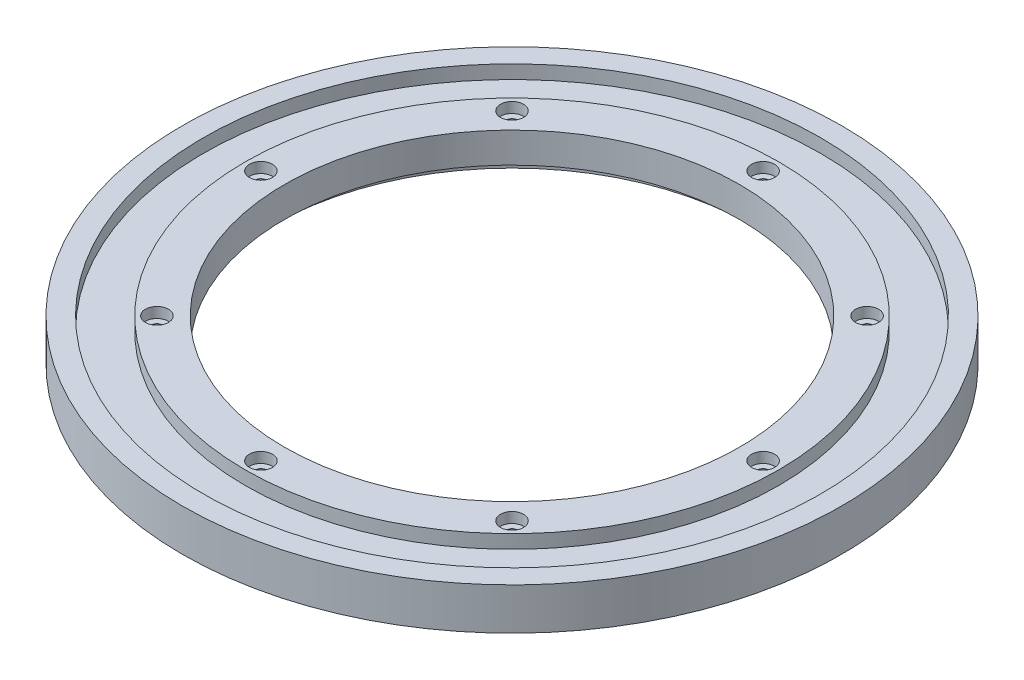
SolidWorks part; units mm, degrees
ref_plane "Front Plane" through (0, 0, 0) normal (0, 0, 1) x (1, 0, 0)
ref_plane "Top Plane" through (0, 0, 0) normal (0, 1, 0) x (1, 0, 0)
ref_plane "Right Plane" through (0, 0, 0) normal (1, 0, 0) x (0, 0, -1)
sketch "Sketch3" plane through (0, 0, 0) normal (1, 0, 0) x (0, 0, -1)
  line L0 (0, -1465.1364) -> (0, 71791.6854) construction
  line L1 (-315, 34.7123) -> (-295, 34.7123)
  line L2 (-295, 34.7123) -> (-295, 21.7123)
  line L3 (-295, 21.7123) -> (-255, 21.7123)
  line L4 (-255, 21.7123) -> (-255, 34.7123)
  line L5 (-255, 34.7123) -> (-217.5, 34.7123)
  line L6 (-217.5, 34.7123) -> (-217.5, 5.7123)
  line L7 (-217.5, 5.7123) -> (-229.5, 5.7123)
  line L8 (-229.5, 5.7123) -> (-229.5, -5.2877)
  line L9 (-229.5, -5.2877) -> (-315, -5.2877)
  line L10 (-315, -5.2877) -> (-315, 34.7123)
  dimension "D1" = 40
  dimension "D2" = 12
  dimension "D3" = 29
  dimension "D4" = 37.5
  dimension "D5" = 40
  dimension "D6" = 13
  dimension "D7" = 11
  dimension "D8" = 20
  dimension "D9" = 510
  dimension "D10" = 590
  dimension "D11" = 27
revolve "Revolve1" add sketch "Sketch3" angle 360 about L0
sketch "Sketch4" plane through (0, 34.7123, 0) normal (0, 1, 0) x (1, 0, 0)
  line L0 (0, -1000) -> (0, 49000) construction
  line L1 (-1000, 0) -> (49000, 0) construction
  circle A0 centre (0, 240) radius 5
  circle A1 centre (0, 0) radius 217.5 construction
  circle A2 centre (169.7056, 169.7056) radius 5
  circle A3 centre (240, 0) radius 5
  circle A4 centre (169.7056, -169.7056) radius 5
  circle A5 centre (0, -240) radius 5
  circle A6 centre (-169.7056, -169.7056) radius 5
  circle A7 centre (-240, 0) radius 5
  circle A8 centre (-169.7056, 169.7056) radius 5
  point P27 (0, 0)
  dimension "D1" = 10
  dimension "D2" = 240
  dimension "D3" = 8
extrude "Cut-Extrude1" cut sketch "Sketch4" against normal through all
sketch "Sketch5" plane through (0, 34.7123, 0) normal (0, 1, 0) x (1, 0, 0)
  circle A0 centre (0, 240) radius 11
  circle A1 centre (169.7056, 169.7056) radius 11
  circle A2 centre (240, 0) radius 11
  circle A3 centre (169.7056, -169.7056) radius 11
  circle A4 centre (0, -240) radius 11
  circle A5 centre (-169.7056, -169.7056) radius 11
  circle A6 centre (-240, 0) radius 11
  circle A7 centre (-169.7056, 169.7056) radius 11
  point P19 (0, 0)
  dimension "D1" = 8
extrude "Cut-Extrude2" cut sketch "Sketch5" against normal blind 10
